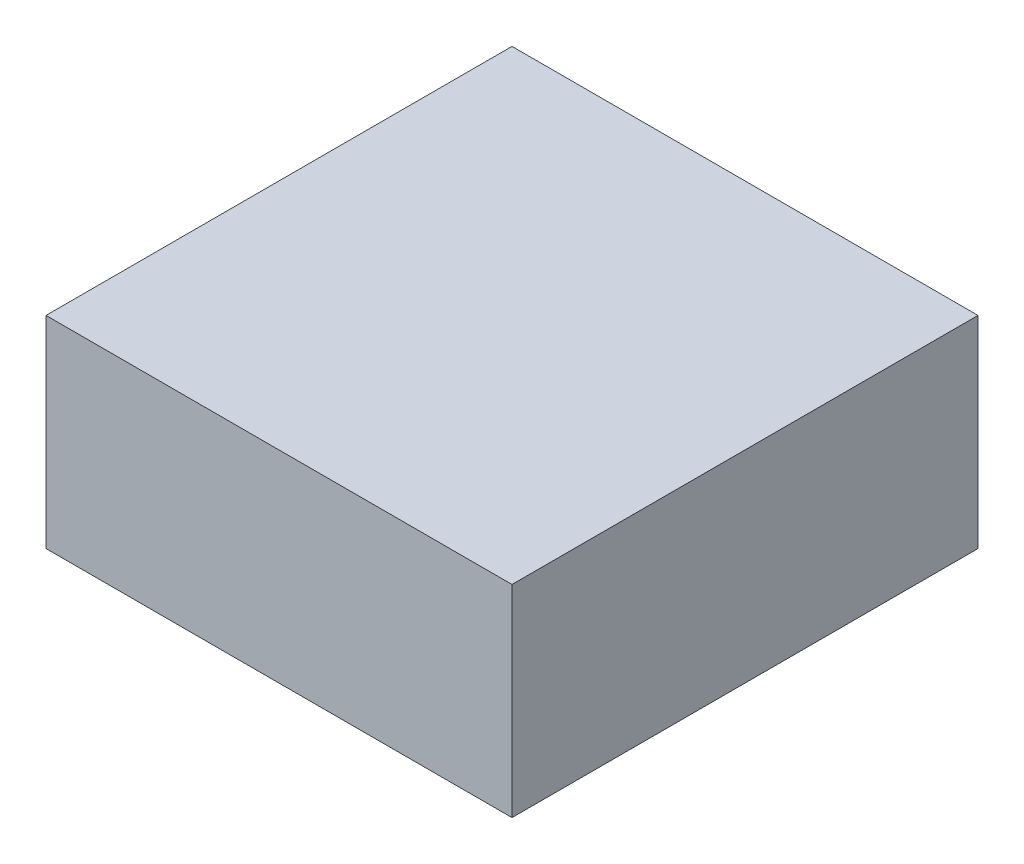
SolidWorks part; units mm, degrees
ref_plane "Front Plane" through (0, 0, 0) normal (0, 0, 1) x (1, 0, 0)
ref_plane "Top Plane" through (0, 0, 0) normal (0, 1, 0) x (1, 0, 0)
ref_plane "Right Plane" through (0, 0, 0) normal (1, 0, 0) x (0, 0, -1)
sketch "Sketch1" plane through (0, 0, 0) normal (0, 1, 0) x (1, 0, 0)
  line L1 (9.525, -9.525) -> (-9.525, -9.525)
  line L2 (9.525, -9.525) -> (9.525, 9.525)
  line L3 (9.525, 9.525) -> (-9.525, 9.525)
  line L4 (-9.525, -9.525) -> (-9.525, 9.525)
  line L5 (9.525, -9.525) -> (-9.525, 9.525) construction
  line L6 (9.525, 9.525) -> (-9.525, -9.525) construction
  point P0 (0, 0)
  dimension "D1" = 19.05
  dimension "D2" = 19.05
extrude "Boss-Extrude1" add sketch "Sketch1" along normal blind 8.255
sketch "Sketch2" plane through (0, 0, 0) normal (0, -1, 0) x (1, 0, 0)
  circle A0 centre (0, 0) radius 9.525
